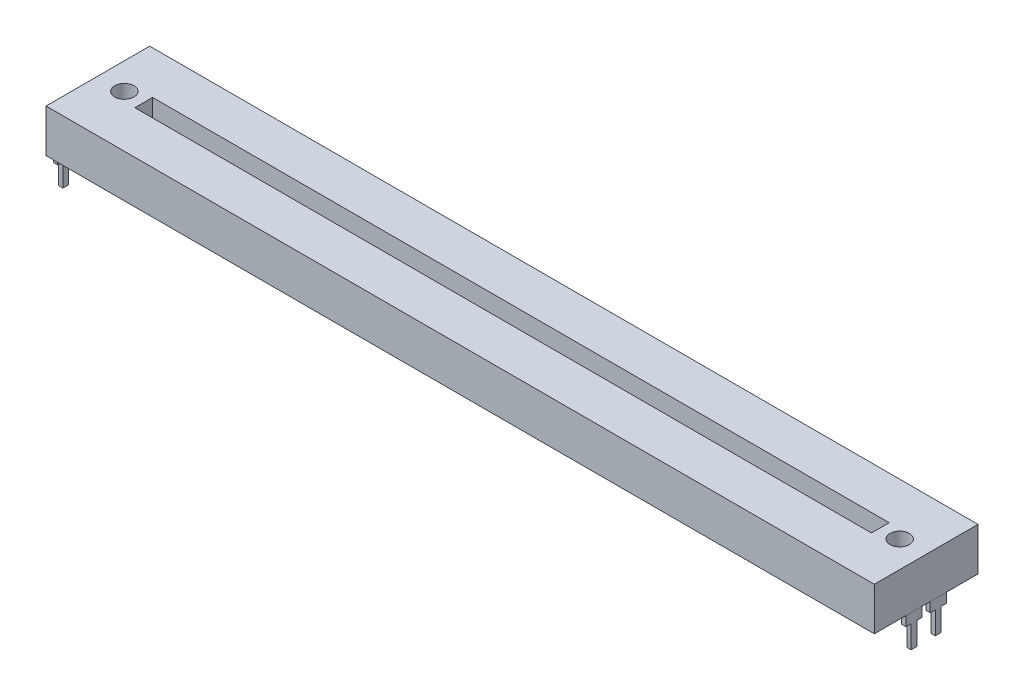
SolidWorks part; units mm, degrees
ref_plane "Front Plane" through (0, 0, 0) normal (0, 0, 1) x (1, 0, 0)
ref_plane "Top Plane" through (0, 0, 0) normal (0, 1, 0) x (1, 0, 0)
ref_plane "Right Plane" through (0, 0, 0) normal (1, 0, 0) x (0, 0, -1)
sketch "Sketch1" plane through (0, 0, 0) normal (0, 1, 0) x (1, 0, 0)
  line L1 (-64.1, 8.025) -> (64.1, 8.025)
  line L2 (-64.1, 8.025) -> (-64.1, -8.025)
  line L3 (-64.1, -8.025) -> (64.1, -8.025)
  line L4 (64.1, 8.025) -> (64.1, -8.025)
  line L5 (-64.1, 8.025) -> (64.1, -8.025) construction
  line L6 (-64.1, -8.025) -> (64.1, 8.025) construction
  point P0 (0, 0)
  dimension "D1" = 16.05
  dimension "D2" = 128.2
extrude "Boss-Extrude1" add sketch "Sketch1" against normal blind 6.65
sketch "Sketch2" plane through (0, 0, 0) normal (0, 1, 0) x (1, 0, 0)
  line L0 (0, 0) -> (0, 8.025) construction
  line L1 (57, 1.375) -> (-57, 1.375)
  line L2 (57, 1.375) -> (57, -1.375)
  line L3 (57, -1.375) -> (-57, -1.375)
  line L4 (-57, 1.375) -> (-57, -1.375)
  line L5 (57, 1.375) -> (-57, -1.375) construction
  line L6 (57, -1.375) -> (-57, 1.375) construction
  line L7 (64.1, 8.025) -> (-64.1, 8.025) construction
  circle A0 centre (-60, 0) radius 1.5
  circle A1 centre (60, 0) radius 1.5
  point P2 (0, 0)
  dimension "D4" = 3
  dimension "D1" = 114
  dimension "D2" = 2.75
  dimension "D3" = 60
extrude "Cut-Extrude1" cut sketch "Sketch2" against normal blind 4
ref_plane "Plane1" through (-64.09, 0, 0) normal (-1, 0, 0) x (0, 0, 1)
sketch "Sketch3" plane through (-64.09, 0, 0) normal (-1, 0, 0) x (0, 0, 1)
  line L0 (-8.025, -6.65) -> (8.025, -6.65) construction
  line L1 (-6.875, -11.65) -> (6.875, -11.65) construction
  line L2 (-6.875, -11.65) -> (-6.875, -6.65) construction
  line L3 (-6.875, -6.65) -> (6.875, -6.65) construction
  line L4 (6.875, -11.65) -> (6.875, -6.65) construction
  line L5 (-6.875, -11.65) -> (6.875, -6.65) construction
  line L6 (-6.875, -6.65) -> (6.875, -11.65) construction
  line L7 (-6.875, -6.65) -> (-6.875, -8.15)
  line L8 (-6.875, -8.15) -> (-6.075, -8.15)
  line L9 (-6.075, -8.15) -> (-6.075, -11.65)
  line L10 (-6.075, -11.65) -> (-5.175, -11.65)
  line L11 (-5.625, -11.65) -> (-5.625, -6.65) construction
  line L12 (-5.175, -8.15) -> (-5.175, -11.65)
  line L13 (-4.375, -8.15) -> (-5.175, -8.15)
  line L14 (-4.375, -6.65) -> (-4.375, -8.15)
  line L15 (-4.375, -6.65) -> (-6.875, -6.65)
  line L16 (-0.625, -6.65) -> (-3.125, -6.65)
  line L17 (-3.125, -6.65) -> (-3.125, -8.15)
  line L18 (-3.125, -8.15) -> (-2.325, -8.15)
  line L19 (-2.325, -8.15) -> (-2.325, -11.65)
  line L20 (-2.325, -11.65) -> (-1.425, -11.65)
  line L21 (-1.425, -8.15) -> (-1.425, -11.65)
  line L22 (-0.625, -8.15) -> (-1.425, -8.15)
  line L23 (-0.625, -6.65) -> (-0.625, -8.15)
  line L24 (3.125, -6.65) -> (0.625, -6.65)
  line L25 (0.625, -6.65) -> (0.625, -8.15)
  line L26 (0.625, -8.15) -> (1.425, -8.15)
  line L27 (1.425, -8.15) -> (1.425, -11.65)
  line L28 (1.425, -11.65) -> (2.325, -11.65)
  line L29 (2.325, -8.15) -> (2.325, -11.65)
  line L30 (3.125, -8.15) -> (2.325, -8.15)
  line L31 (3.125, -6.65) -> (3.125, -8.15)
  line L32 (6.875, -6.65) -> (4.375, -6.65)
  line L33 (4.375, -6.65) -> (4.375, -8.15)
  line L34 (4.375, -8.15) -> (5.175, -8.15)
  line L35 (5.175, -8.15) -> (5.175, -11.65)
  line L36 (5.175, -11.65) -> (6.075, -11.65)
  line L37 (6.075, -8.15) -> (6.075, -11.65)
  line L38 (6.875, -8.15) -> (6.075, -8.15)
  line L39 (6.875, -6.65) -> (6.875, -8.15)
  point P0 (0, -9.15)
  point P17 (-4.375, -7.4)
  dimension "D1" = 13.75
  dimension "D2" = 5
  dimension "D3" = 1.5
  dimension "D4" = 0.45
  dimension "D5" = 2.5
  dimension "D7" = 3.75
  dimension "D6" = 4
extrude "Boss-Extrude2" add sketch "Sketch3" against normal blind 0.65
ref_plane "Plane2" through (64.09, 0, 0) normal (1, 0, 0) x (0, 0, -1)
sketch "Sketch4" plane through (64.09, 0, 0) normal (1, 0, 0) x (0, 0, -1)
  line L0 (-0.625, -8.15) -> (-0.625, -6.65) construction
  line L1 (-0.625, -6.65) -> (-3.125, -6.65) construction
  line L2 (-3.125, -6.65) -> (-3.125, -8.15) construction
  line L3 (-3.125, -8.15) -> (-2.325, -8.15) construction
  line L4 (-2.325, -8.15) -> (-2.325, -11.65) construction
  line L5 (-2.325, -11.65) -> (-1.425, -11.65) construction
  line L6 (-1.425, -11.65) -> (-1.425, -8.15) construction
  line L7 (-1.425, -8.15) -> (-0.625, -8.15) construction
  line L8 (3.125, -8.15) -> (3.125, -6.65) construction
  line L9 (3.125, -6.65) -> (0.625, -6.65) construction
  line L10 (0.625, -6.65) -> (0.625, -8.15) construction
  line L11 (0.625, -8.15) -> (1.425, -8.15) construction
  line L12 (1.425, -8.15) -> (1.425, -11.65) construction
  line L13 (1.425, -11.65) -> (2.325, -11.65) construction
  line L14 (2.325, -11.65) -> (2.325, -8.15) construction
  line L15 (2.325, -8.15) -> (3.125, -8.15) construction
  line L16 (-0.625, -8.15) -> (-0.625, -6.65)
  line L17 (-0.625, -6.65) -> (-3.125, -6.65)
  line L18 (-3.125, -6.65) -> (-3.125, -8.15)
  line L19 (-3.125, -8.15) -> (-2.325, -8.15)
  line L20 (-2.325, -8.15) -> (-2.325, -11.65)
  line L21 (-2.325, -11.65) -> (-1.425, -11.65)
  line L22 (-1.425, -11.65) -> (-1.425, -8.15)
  line L23 (-1.425, -8.15) -> (-0.625, -8.15)
  line L24 (3.125, -8.15) -> (3.125, -6.65)
  line L25 (3.125, -6.65) -> (0.625, -6.65)
  line L26 (0.625, -6.65) -> (0.625, -8.15)
  line L27 (0.625, -8.15) -> (1.425, -8.15)
  line L28 (1.425, -8.15) -> (1.425, -11.65)
  line L29 (1.425, -11.65) -> (2.325, -11.65)
  line L30 (2.325, -11.65) -> (2.325, -8.15)
  line L31 (2.325, -8.15) -> (3.125, -8.15)
extrude "Boss-Extrude3" add sketch "Sketch4" against normal blind 0.65
ref_plane "Plane3" through (-50, 0, 0) normal (1, 0, 0) x (0, 0, -1)
ref_plane "Plane4" through (50, 0, 0) normal (1, 0, 0) x (0, 0, -1)
ref_plane "Plane5" through (-63.765, 0, 0) normal (-1, 0, 0) x (0, 0, 1)
